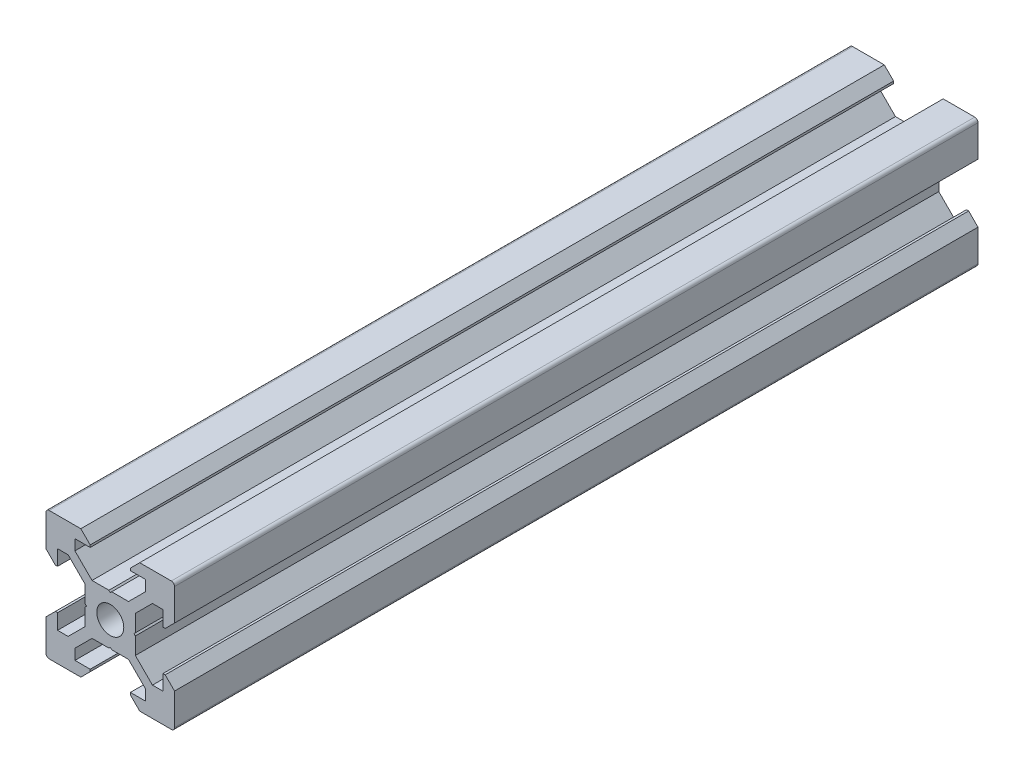
SolidWorks part; units mm, degrees
material "6061-T6 (SS)"
ref_plane "Front Plane" through (0, 0, 0) normal (0, 0, 1) x (1, 0, 0)
ref_plane "Top Plane" through (0, 0, 0) normal (0, 1, 0) x (1, 0, 0)
ref_plane "Right Plane" through (0, 0, 0) normal (1, 0, 0) x (0, 0, -1)
sketch "Sketch1" plane through (0, 0, 0) normal (0, 0, 1) x (1, 0, 0)
  line L1 (9.5, -10) -> (-9.5, -10)
  line L2 (10, -9.5) -> (10, 9.5)
  line L3 (9.5, 10) -> (-9.5, 10)
  line L4 (-10, -9.5) -> (-10, 9.5)
  line L5 (10, -10) -> (-10, 10) construction
  line L6 (10, 10) -> (-10, -10) construction
  circle A0 centre (0, 0) radius 2.1
  arc A1 (-9.5, 10) -> (-10, 9.5) centre (-9.5, 9.5) ccw
  arc A2 (10, 9.5) -> (9.5, 10) centre (9.5, 9.5) ccw
  arc A3 (9.5, -10) -> (10, -9.5) centre (9.5, -9.5) ccw
  arc A4 (-9.5, -10) -> (-10, -9.5) centre (-9.5, -9.5) cw
  point P0 (0, 0)
  line B0 (0, 0) -> (0, 10) construction
  line B1 (0, 3.69) -> (-0.21, 3.9)
  line B2 (-0.21, 3.9) -> (-2.8393, 3.9)
  line B3 (-2.8393, 3.9) -> (-5.5, 6.5607)
  line B4 (-5.5, 6.5607) -> (-5.5, 8.2)
  line B5 (-5.5, 8.2) -> (-3.125, 8.2)
  line B6 (-3.125, 8.2) -> (-3.125, 8.545)
  line B7 (-3.125, 8.545) -> (-4.58, 10)
  line B8 (-4.58, 10) -> (4.58, 10)
  line B9 (0, 0) -> (-5.9132, 5.9132) construction
  line B10 (3.125, 8.545) -> (4.58, 10)
  line B11 (3.125, 8.2) -> (3.125, 8.545)
  line B12 (5.5, 8.2) -> (3.125, 8.2)
  line B13 (5.5, 6.5607) -> (5.5, 8.2)
  line B14 (2.8393, 3.9) -> (5.5, 6.5607)
  line B15 (0.21, 3.9) -> (2.8393, 3.9)
  line B16 (0, 3.69) -> (0.21, 3.9)
  line B17 (0, 0) -> (-10, 0) construction
  line B18 (-3.69, 0) -> (-3.9, -0.21)
  line B19 (-3.9, -0.21) -> (-3.9, -2.8393)
  line B20 (-3.9, -2.8393) -> (-6.5607, -5.5)
  line B21 (-6.5607, -5.5) -> (-8.2, -5.5)
  line B22 (-8.2, -5.5) -> (-8.2, -3.125)
  line B23 (-8.2, -3.125) -> (-8.545, -3.125)
  line B24 (-8.545, -3.125) -> (-10, -4.58)
  line B25 (-10, -4.58) -> (-10, 4.58)
  line B26 (0, 0) -> (-5.9132, -5.9132) construction
  line B27 (-8.545, 3.125) -> (-10, 4.58)
  line B28 (-8.2, 3.125) -> (-8.545, 3.125)
  line B29 (-8.2, 5.5) -> (-8.2, 3.125)
  line B30 (-6.5607, 5.5) -> (-8.2, 5.5)
  line B31 (-3.9, 2.8393) -> (-6.5607, 5.5)
  line B32 (-3.9, 0.21) -> (-3.9, 2.8393)
  line B33 (-3.69, 0) -> (-3.9, 0.21)
  line B34 (0, 0) -> (0, -10) construction
  line B35 (0, -3.69) -> (0.21, -3.9)
  line B36 (0.21, -3.9) -> (2.8393, -3.9)
  line B37 (2.8393, -3.9) -> (5.5, -6.5607)
  line B38 (5.5, -6.5607) -> (5.5, -8.2)
  line B39 (5.5, -8.2) -> (3.125, -8.2)
  line B40 (3.125, -8.2) -> (3.125, -8.545)
  line B41 (3.125, -8.545) -> (4.58, -10)
  line B42 (4.58, -10) -> (-4.58, -10)
  line B43 (0, 0) -> (5.9132, -5.9132) construction
  line B44 (-3.125, -8.545) -> (-4.58, -10)
  line B45 (-3.125, -8.2) -> (-3.125, -8.545)
  line B46 (-5.5, -8.2) -> (-3.125, -8.2)
  line B47 (-5.5, -6.5607) -> (-5.5, -8.2)
  line B48 (-2.8393, -3.9) -> (-5.5, -6.5607)
  line B49 (-0.21, -3.9) -> (-2.8393, -3.9)
  line B50 (0, -3.69) -> (-0.21, -3.9)
  line B51 (0, 0) -> (10, 0) construction
  line B52 (3.69, 0) -> (3.9, 0.21)
  line B53 (3.9, 0.21) -> (3.9, 2.8393)
  line B54 (3.9, 2.8393) -> (6.5607, 5.5)
  line B55 (6.5607, 5.5) -> (8.2, 5.5)
  line B56 (8.2, 5.5) -> (8.2, 3.125)
  line B57 (8.2, 3.125) -> (8.545, 3.125)
  line B58 (8.545, 3.125) -> (10, 4.58)
  line B59 (10, 4.58) -> (10, -4.58)
  line B60 (0, 0) -> (5.9132, 5.9132) construction
  line B61 (8.545, -3.125) -> (10, -4.58)
  line B62 (8.2, -3.125) -> (8.545, -3.125)
  line B63 (8.2, -5.5) -> (8.2, -3.125)
  line B64 (6.5607, -5.5) -> (8.2, -5.5)
  line B65 (3.9, -2.8393) -> (6.5607, -5.5)
  line B66 (3.9, -0.21) -> (3.9, -2.8393)
  line B67 (3.69, 0) -> (3.9, -0.21)
  dimension "D1" = 4.2
  dimension "D3" = 0.5
  dimension "D2" = 20
sketch_block_instance "V Slot 1-4"
sketch_block "V Slot 1" parameters "D1"=10, "D2"=11, "D3"=4.3, "D4"=1.8, "D5"=0.21, "D6"=45, "D7"=9.16, "D8"=1.5, "D9"=6.25
sketch_block_instance "V Slot 1-5"
sketch_block_instance "V Slot 1-6"
sketch_block_instance "V Slot 1-7"
extrude "Boss-Extrude1" add sketch "Sketch1" along normal blind 125 contours B67 B52 B53 B54 B55 B56 B57 B58 L2 A2 L3 B10 B11 B12 B13 B14 B15 B16 B1 B2 B3 B4 B5 B6 B7 A1 L4 B27 B28 B29 B30 B31 B32 B33 B18 B19 B20 B21 B22 B23 B24 A4 L1 B44 B45 B46 B47 B48 B49
